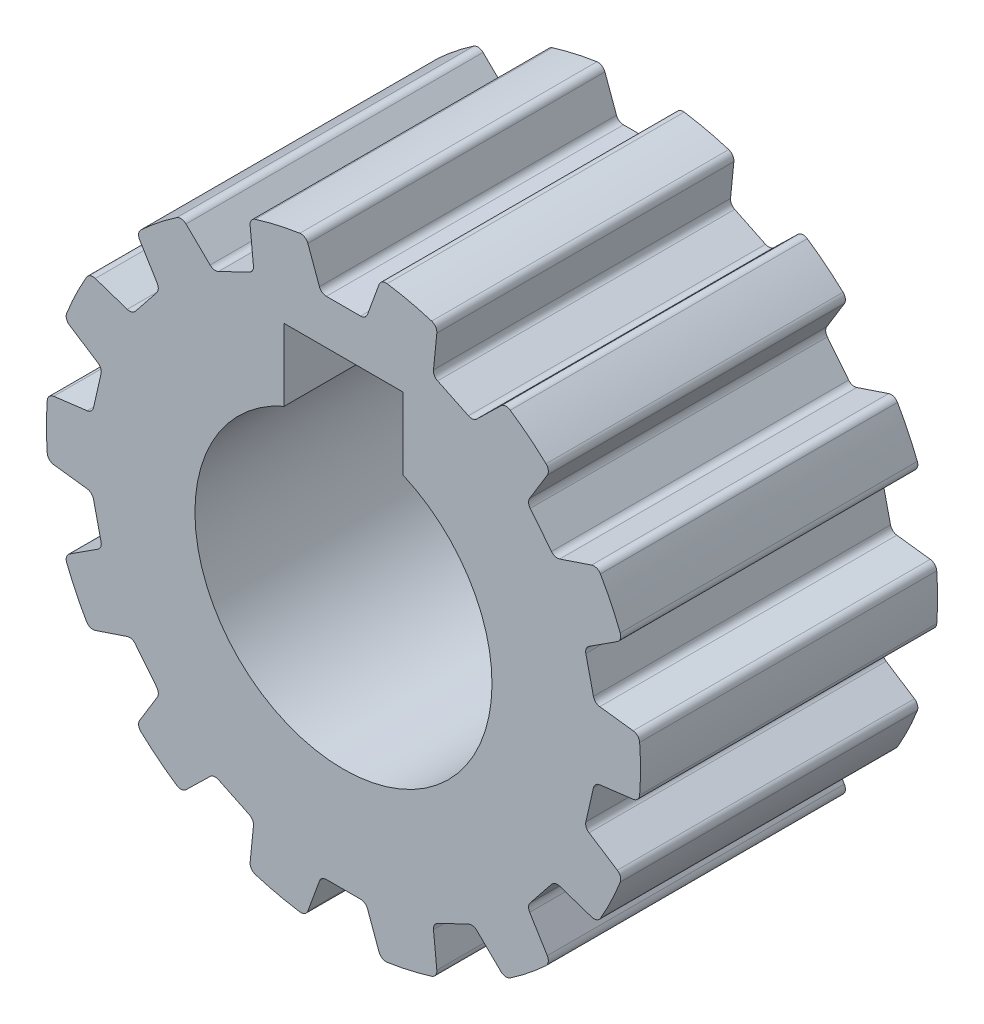
SolidWorks part; units mm, degrees
ref_plane "Front Plane" through (0, 0, 0) normal (0, 0, 1) x (1, 0, 0)
ref_plane "Top Plane" through (0, 0, 0) normal (0, 1, 0) x (1, 0, 0)
ref_plane "Right Plane" through (0, 0, 0) normal (1, 0, 0) x (0, 0, -1)
sketch "Sketch1" plane through (0, 0, 0) normal (0, 0, 1) x (1, 0, 0)
  line L1 (-1.9941, 7) -> (2.0059, 7)
  line L2 (-1.9941, 7) -> (-1.9941, 4.5851)
  line L4 (2.0059, 7) -> (2.0059, 4.58)
  arc A0 (-1.9941, 4.5851) -> (2.0059, 4.58) centre (0, 0) ccw
  circle A1 centre (0, 0) radius 10
  point P3 (0, 5)
  dimension "D1" = 10
  dimension "D5" = 20
  dimension "D2" = 4
  dimension "D3" = 7
  dimension "D4" = 2.42
extrude "Boss-Extrude1" add sketch "Sketch1" along normal mid plane 10
sketch "Sketch2" plane through (0, 0, 5) normal (0, 0, 1) x (1, 0, 0)
  line L0 (0, 10) -> (0, 0) construction
  line L1 (-0.75, 8.5) -> (0.75, 8.5)
  line L2 (0.75, 8.5) -> (1.2666, 9.9195)
  line L3 (-0.75, 8.5) -> (-1.2666, 9.9195)
  circle A0 centre (0, 0) radius 10 construction
  arc A1 (-1.2666, 9.9195) -> (1.2666, 9.9195) centre (0, 9.116) cw
  point P10 (0, 8.5)
  dimension "D3" = 1.5
  dimension "D1" = 0.75
  dimension "D2" = 20
  dimension "D4" = 8.5
extrude "Cut-Extrude1" cut sketch "Sketch2" against normal through all
pattern_circular "CirPattern1" count 14 over 360 about axis through (0, 0, 0) along (0, 0, 1) of "Cut-Extrude1"
fillet "Fillet1" radius 0.25 56 edges at (-7.1132, 4.7133, 0) (-8.5451, 5.1944, 0) (-9.3889, 3.4422, 0) (-8.12, 2.6226, 0) (-8.4538, 1.1602, 0) (-9.9526, 0.9724, 0) (-9.9526, -0.9724, 0) (-8.4538, -1.1602, 0) (-8.12, -2.6226, 0) (-9.3889, -3.4422, 0) (-8.5451, -5.1944, 0) (-7.1132, -4.7133, 0) (-6.178, -5.886, 0) (-6.9656, -7.175, 0) (-5.4451, -8.3875, 0) (-4.3637, -7.3328, 0) (-3.0123, -7.9836, 0) (-3.1627, -9.4867, 0) (-1.2666, -9.9195, 0) (-0.75, -8.5, 0) (0.75, -8.5, 0) (1.2666, -9.9195, 0) (3.1627, -9.4867, 0) (3.0123, -7.9836, 0) (4.3637, -7.3328, 0) (5.4451, -8.3875, 0) (6.9656, -7.175, 0) (6.178, -5.886, 0) (7.1132, -4.7133, 0) (8.5451, -5.1944, 0) (9.3889, -3.4422, 0) (8.12, -2.6226, 0) (8.4538, -1.1602, 0) (9.9526, -0.9724, 0) (9.9526, 0.9724, 0) (8.4538, 1.1602, 0) (8.12, 2.6226, 0) (9.3889, 3.4422, 0) (8.5451, 5.1944, 0) (7.1132, 4.7133, 0) (6.178, 5.886, 0) (6.9656, 7.175, 0) (5.4451, 8.3875, 0) (4.3637, 7.3328, 0) (3.0123, 7.9836, 0) (3.1627, 9.4867, 0) (1.2666, 9.9195, 0) (0.75, 8.5, 0) (-0.75, 8.5, 0) (-1.2666, 9.9195, 0) (-3.0123, 7.9836, 0) (-4.3637, 7.3328, 0) (-5.4451, 8.3875, 0) (-6.9656, 7.175, 0) (-6.178, 5.886, 0) (-3.1627, 9.4867, 0)
